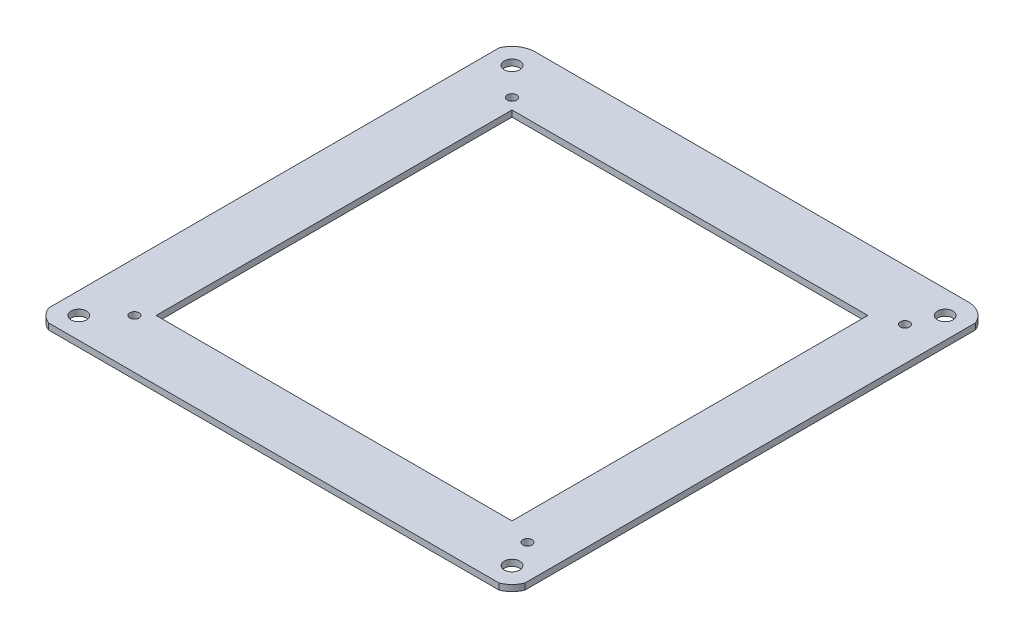
SolidWorks part; units mm, degrees
ref_plane "Alzado" through (0, 0, 0) normal (0, 0, 1) x (1, 0, 0)
ref_plane "Planta" through (0, 0, 0) normal (0, 1, 0) x (1, 0, 0)
ref_plane "Vista lateral" through (0, 0, 0) normal (1, 0, 0) x (0, 0, -1)
sketch "Croquis1" plane through (0, 0, 0) normal (0, 1, 0) x (1, 0, 0)
  line L0 (-80, 80) -> (80, 80)
  line L1 (-70, -70) -> (70, -70) construction
  line L2 (-70, -70) -> (-70, 70) construction
  line L3 (-70, 70) -> (70, 70) construction
  line L4 (70, -70) -> (70, 70) construction
  line L5 (-70, -70) -> (70, 70) construction
  line L6 (-70, 70) -> (70, -70) construction
  line L7 (80, -80) -> (80, 80)
  line L8 (-80, -80) -> (80, -80)
  line L9 (-80, -80) -> (-80, 80)
  line L10 (-61, 0) -> (-61, -61) construction
  line L11 (0, 0) -> (-61, 0) construction
  line L12 (0, 0) -> (0, 61) construction
  line L13 (0, 61) -> (-61, 61) construction
  line L14 (-61, 0) -> (-61, 61) construction
  line L15 (0, 0) -> (66, 0)
  line L16 (0, 0) -> (0, 61)
  line L17 (0, 61) -> (66, 61) construction
  line L18 (66, 0) -> (66, 61) construction
  line L19 (-61, -61) -> (66, -61) construction
  line L20 (66, -61) -> (66, 0) construction
  line L22 (-57.5, -57.5) -> (57.5, -57.5)
  line L23 (-57.5, -57.5) -> (-57.5, 57.5)
  line L24 (-57.5, 57.5) -> (57.5, 57.5)
  line L25 (57.5, -57.5) -> (57.5, 57.5)
  line L26 (-57.5, -57.5) -> (57.5, 57.5) construction
  line L27 (-57.5, 57.5) -> (57.5, -57.5) construction
  circle A0 centre (-70, 70) radius 2.5
  circle A1 centre (70, 70) radius 2.5
  circle A2 centre (70, -70) radius 2.5
  circle A3 centre (-70, -70) radius 2.5
  circle A4 centre (-61, 61) radius 1.5
  circle A5 centre (66, 61) radius 1.5
  circle A6 centre (66, -61) radius 1.5
  circle A7 centre (-61, -61) radius 1.5
  point P0 (0, 0)
  dimension "D3" = 5
  dimension "D6" = 3
  dimension "D1" = 140
  dimension "D2" = 10
  dimension "D4" = 61
  dimension "D5" = 66
  dimension "D7" = 115
extrude "Saliente-Extruir1" add sketch "Croquis1" along normal blind 2
sketch "Croquis2" plane through (0, 2, 0) normal (0, 1, 0) x (1, 0, 0)
  line L0 (-70, 70) -> (70, -70) construction
  line L1 (-70, 70) -> (-85, 85) construction
  line L2 (-85, 85) -> (85, 85) construction
  line L3 (-85, 85) -> (-85, -85) construction
  line L4 (-85, -85) -> (85, -85) construction
  line L5 (85, 85) -> (85, -85) construction
  line L6 (70, -70) -> (85, -85) construction
  dimension "D1" = 170
sketch "Croquis3" plane through (0, 2, 0) normal (0, 1, 0) x (1, 0, 0)
  line L0 (-70, 70) -> (70, -70) construction
  line L1 (72.7854, -76.9636) -> (-72.7854, -76.9636)
  line L2 (76.9636, -72.7854) -> (76.9636, 72.7854)
  line L3 (70, 77.5) -> (-70, 77.5)
  line L4 (-76.9636, -72.7854) -> (-76.9636, 72.7854)
  line L5 (80, -80) -> (-80, 80) construction
  line L6 (80, 80) -> (-80, -80) construction
  line L7 (-85, -85) -> (85, -85) construction
  line L8 (-85, 85) -> (-85, -85) construction
  line L9 (-85, 85) -> (85, 85) construction
  line L10 (85, 85) -> (85, -85) construction
  line L11 (-85, -85) -> (85, -85)
  line L12 (-85, 85) -> (-85, -85)
  line L13 (-85, 85) -> (85, 85)
  line L14 (85, 85) -> (85, -85)
  arc A0 (-70, 77.5) -> (-76.9636, 72.7854) centre (-70, 70) ccw
  arc A1 (76.9636, 72.7854) -> (70, 77.5) centre (70, 70) ccw
  arc A2 (72.7854, -76.9636) -> (76.9636, -72.7854) centre (70, -70) ccw
  arc A3 (-76.9636, -72.7854) -> (-72.7854, -76.9636) centre (-70, -70) ccw
  point P3 (0, 0)
  dimension "D1" = 15
extrude "Cortar-Extruir1" cut sketch "Croquis3" against normal blind 10
